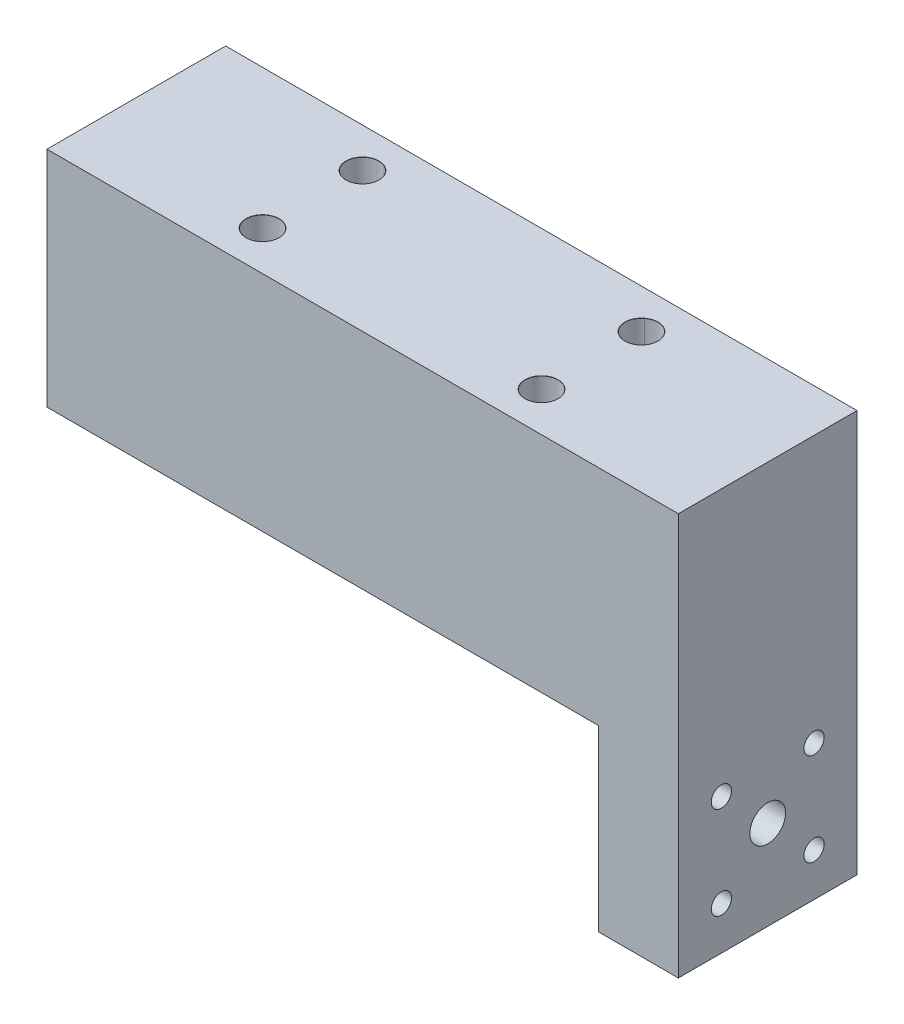
SolidWorks part; units mm, degrees
ref_plane "Front Plane" through (0, 0, 0) normal (0, 0, 1) x (1, 0, 0)
ref_plane "Top Plane" through (0, 0, 0) normal (0, 1, 0) x (1, 0, 0)
ref_plane "Right Plane" through (0, 0, 0) normal (1, 0, 0) x (0, 0, -1)
sketch "Sketch1" plane through (0, 0, 0) normal (0, 0, 1) x (1, 0, 0)
  line L1 (-60.206, 27.9097) -> (45.794, 27.9097)
  line L2 (-60.206, 27.9097) -> (-60.206, -39.5903)
  line L3 (-60.206, -39.5903) -> (45.794, -39.5903)
  line L4 (45.794, 27.9097) -> (45.794, -39.5903)
  dimension "D1" = 106
  dimension "D2" = 67.5
extrude "Boss-Extrude1" add sketch "Sketch1" along normal blind 30
sketch "Sketch2" plane through (0, 0, 0) normal (0, 0, 1) x (1, 0, 0)
  line L1 (-60.206, -39.5903) -> (32.394, -39.5903)
  line L2 (-60.206, -39.5903) -> (-60.206, -9.5903)
  line L3 (-60.206, -9.5903) -> (32.394, -9.5903)
  line L4 (32.394, -39.5903) -> (32.394, -9.5903)
  dimension "D1" = 30
  dimension "D2" = 92.6
extrude "Boss-Extrude2" add sketch "Sketch2" along normal blind 30
sketch "Sketch3" plane through (0, 0, 0) normal (0, 0, 1) x (1, 0, 0)
  line L1 (-60.206, -39.5903) -> (32.394, -39.5903)
  line L2 (-60.206, -39.5903) -> (-60.206, -9.5903)
  line L3 (-60.206, -9.5903) -> (32.394, -9.5903)
  line L4 (32.394, -39.5903) -> (32.394, -9.5903)
  dimension "D1" = 92.6
  dimension "D2" = 30
extrude "Cut-Extrude1" cut sketch "Sketch3" along normal blind 30
sketch "Sketch4" plane through (45.794, 0, 0) normal (1, 0, 0) x (0, 0, -1)
  circle A0 centre (-15, -24.5903) radius 3
  dimension "D1" = 6
extrude "Cut-Extrude2" cut sketch "Sketch4" against normal blind 30
hole_wizard "M3 Clearance Hole1" positions "Sketch9" profile "Sketch10" hole size "M3" standard "ISO" end condition through all
sketch "Sketch9" plane through (32.394, 0, 0) normal (-1, 0, 0) x (0, 0, 1)
  line L0 (0, -9.5903) -> (30, -39.5903) construction
  line L1 (30, -39.5903) -> (0, -39.5903) construction
  line L2 (30, -39.5903) -> (30, -9.5903) construction
  line L4 (30, -9.5903) -> (0, -39.5903) construction
  circle A0 centre (15, -24.5903) radius 11 construction
  point P17 (7.2218, -16.8121)
  point P19 (22.7782, -16.8121)
  point P21 (22.7782, -32.3685)
  point P23 (7.2218, -32.3685)
  dimension "D1" = 22
sketch "Sketch10" plane through (32.394, -32.3685, 7.2218) normal (0, 1, 0) x (0, 0, 1)
  line L0 (0, 0) -> (0, 13.4)
  line L1 (0, 13.4) -> (1.7, 13.4)
  line L2 (1.7, 13.4) -> (1.7, 0.025)
  line L3 (1.7, 0.025) -> (1.725, 0)
  line L5 (1.725, 0) -> (0, 0)
  line L6 (-1.7, 0.025) -> (-1.725, 0) construction
  line L11 (0, -6.35) -> (0, 107.95) construction
  dimension "Thru Hole Dia." = 3.4
  dimension "Thru Hole Depth" = 13.4
  dimension "Near C'Sink Dia." = 3.45
  dimension "Near C'Sink Angle" = 90
sketch "Sketch11" plane through (32.394, 0, 0) normal (-1, 0, 0) x (0, 0, 1)
  circle A0 centre (15, -24.5903) radius 9
  dimension "D1" = 18
extrude "Cut-Extrude3" cut sketch "Sketch11" against normal blind 2
hole_wizard "M5 Clearance Hole1" positions "3DSketch2" profile "Sketch12" hole size "M5" standard "ISO"
sketch3d "3DSketch2"
  point P10 (16.2122, 27.9097, 6.6142)
  point P213 (-30.6242, 27.9097, 23.3858)
  point P214 (16.2122, 27.9097, 23.3858)
  point P215 (-30.6242, 27.9097, 6.6142)
  point P225 (-30.6242, 27.9097, 6.6142)
  point P229 (-30.6242, 27.9097, 6.6142)
  point P230 (16.2122, 27.9097, 6.6142)
  point P232 (16.2122, 27.9097, 23.3858)
  point P233 (-30.6242, 27.9097, 23.3858)
  point P247 (-30.6242, 27.9097, 6.6142)
  point P248 (-30.6242, 27.9097, 6.6142)
  point P250 (-30.6242, 27.9097, 6.6142)
  point P251 (-30.6242, 27.9097, 6.6142)
  point P260 (16.2122, 27.9097, 6.6142)
  point P262 (-30.6242, 27.9097, 6.6142)
  point P263 (-30.6242, 27.9097, 6.6142)
  point P265 (-30.6242, 27.9097, 6.6142)
  point P267 (16.2122, 27.9097, 6.6142)
  point P269 (16.2122, 27.9097, 6.6142)
  point P271 (16.2122, 27.9097, 23.3858)
  point P272 (-30.6242, 27.9097, 23.3858)
sketch "Sketch12" plane through (-30.6242, 27.9097, 23.3858) normal (1, 0, 0) x (0, 0, 1)
  line L0 (0, 0) -> (0, 67.5)
  line L1 (0, 67.5) -> (2.75, 67.5)
  line L2 (2.75, 67.5) -> (2.75, 0.025)
  line L3 (2.75, 0.025) -> (2.775, 0)
  line L5 (2.775, 0) -> (0, 0)
  line L6 (-2.75, 0.025) -> (-2.775, 0) construction
  line L11 (0, -6.35) -> (0, 107.95) construction
  dimension "Thru Hole Dia." = 5.5
  dimension "Thru Hole Depth" = 67.5
  dimension "Near C'Sink Dia." = 5.55
  dimension "Near C'Sink Angle" = 90
equation "\"L1\"= 30mm"
equation "\"L2\"= 92.6mm"
equation "\"Base\"= 30mm"
equation "\"WallHeight\"= 37.5mm"
equation "\"MotorRecessDia\"= 18mm"
equation "\"BoltCircle\"= 22mm"
equation "\"MotorRecessDepth\"= 2mm"
equation "\"D1@Sketch9\"=\"BoltCircle\""
equation "\"ShaftDia\"= 6mm"
equation "\"D1@Cut-Extrude3\"=\"MotorRecessDepth\""
equation "\"D1@Cut-Extrude2\"=\"L1\""
equation "\"D1@Boss-Extrude1\"=\"Base\""
equation "\"D1@Boss-Extrude2\"=\"L1\""
equation "\"D1@Cut-Extrude1\"=\"Base\""
equation "\"D1@Sketch4\"=\"ShaftDia\""
equation "\"D1@Sketch11\"=\"MotorRecessDia\""
equation "\"TotalY\"= 67.5mm"
equation "\"TotalX\"= 106mm"
equation "\"D1@Sketch1\"=\"TotalX\""
equation "\"D2@Sketch1\"=\"TotalY\""
equation "\"D2@Sketch2\"=\"L2\""
equation "\"D1@Sketch2\"=\"Base\""
equation "\"D1@Sketch3\"=\"L2\""
equation "\"D2@Sketch3\"=\"L1\""
equation "\"MotorHeight\"= 13.4mm"
equation "\"Thru Hole Depth@Sketch10\"=\"MotorHeight\""
equation "\"SF\"= 3"
equation "\"P\"= 300"
equation "\"E\" = 2000"
equation "\"StressY\"= 30000000"
equation "\"StressAllowed\" = 10mm"
equation "\"DeflectMAX\"= 0.0003m"
equation "\"BendingStressFEAT1\"= sqr ( ( 6 * \"P\" * \"L1\" ) / ( \"Base\" * \"StressAllowed\" ) )"
equation "\"DeflectionFEAT2\"= ( ( 4 * \"P\" * \"L2\" ^ 3 ) / ( \"E\" * \"Base\" * \"DeflectMAX\" ) ) ^ ( 1 / 3 )"
equation "\"BendingStressFEAT2\" = sqr ( ( 6 * \"P\" * \"L2\" ) / ( \"Base\" * \"StressAllowed\" ) )"
equation "\"DeflectionFEAT1\"= ( ( 4 * \"P\" * \"L1\" ^ 3 ) / ( \"E\" * \"Base\" * \"DeflectMAX\" ) ) ^ ( 1 / 3 )"
